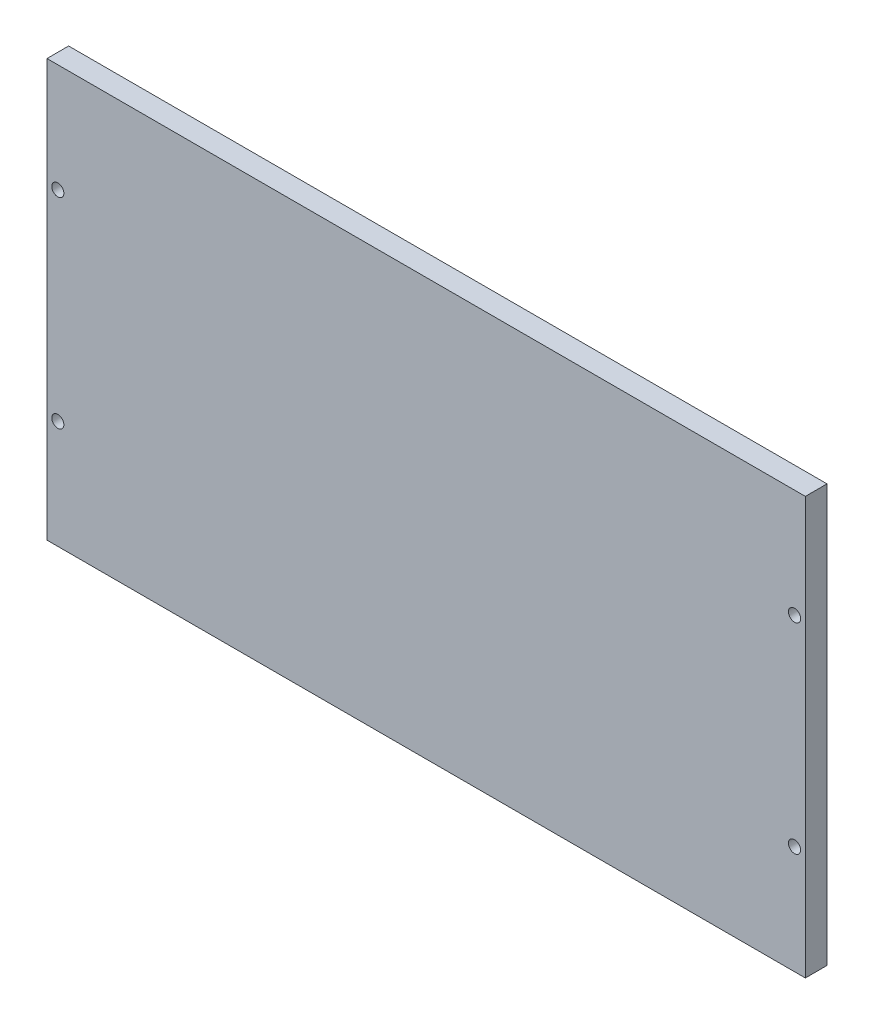
SolidWorks part; units mm, degrees
ref_plane "Front Plane" through (0, 0, 0) normal (0, 0, 1) x (1, 0, 0)
ref_plane "Top Plane" through (0, 0, 0) normal (0, 1, 0) x (1, 0, 0)
ref_plane "Right Plane" through (0, 0, 0) normal (1, 0, 0) x (0, 0, -1)
sketch "Sketch1" plane through (0, 0, 0) normal (0, 0, 1) x (1, 0, 0)
  line L1 (0, 0) -> (177.8, 0)
  line L2 (0, 0) -> (0, 97.79)
  line L3 (0, 97.79) -> (177.8, 97.79)
  line L4 (177.8, 0) -> (177.8, 97.79)
  dimension "D1" = 177.8
  dimension "D2" = 97.79
extrude "Boss-Extrude1" add sketch "Sketch1" along normal blind 5.08
sketch "Sketch2" plane through (0, 0, 5.08) normal (0, 0, 1) x (1, 0, 0)
  line L0 (2.54, 97.79) -> (2.54, 0) construction
  line L1 (177.8, 97.79) -> (0, 97.79) construction
  line L2 (0, 0) -> (177.8, 0) construction
  line L3 (0, 97.79) -> (0, 0) construction
  line L4 (175.26, 97.79) -> (175.26, 0) construction
  line L5 (177.8, 0) -> (177.8, 97.79) construction
  circle A0 centre (2.54, 72.39) radius 1.4224
  circle A1 centre (2.54, 25.4) radius 1.4224
  circle A3 centre (175.26, 25.4) radius 1.4224
  circle A4 centre (175.26, 72.39) radius 1.4224
  dimension "D3" = 25.4
  dimension "D5" = 25.4
  dimension "D6" = 46.99
  dimension "D1" = 2.54
  dimension "D2" = 2.54
  dimension "D4" = 46.99
extrude "Cut-Extrude1" cut sketch "Sketch2" against normal blind 25.4
